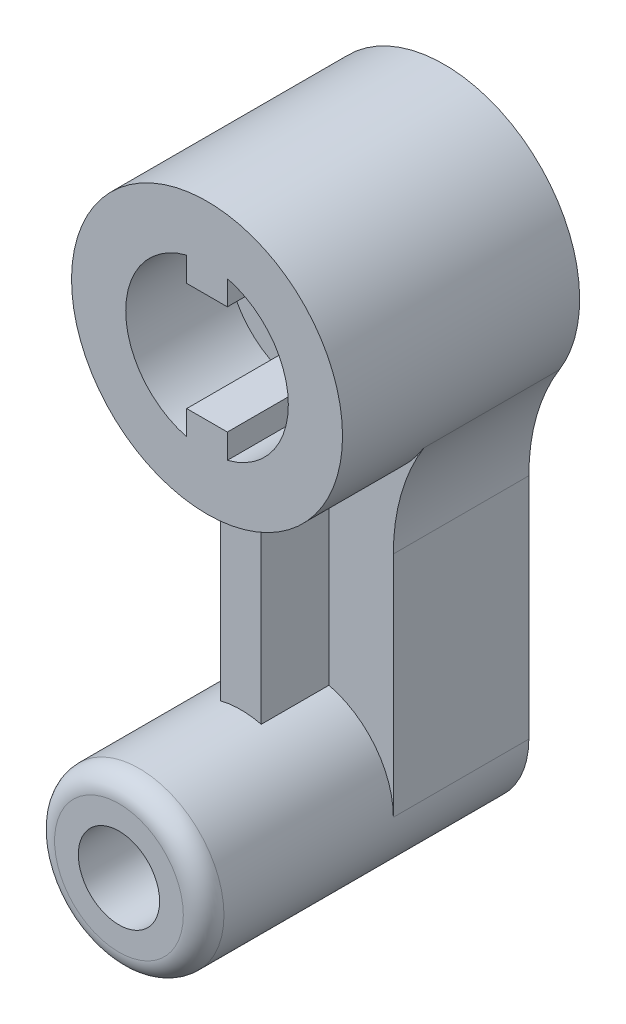
SolidWorks part; units mm, degrees
ref_plane "Alzado" through (0, 0, 0) normal (0, 0, 1) x (1, 0, 0)
ref_plane "Planta" through (0, 0, 0) normal (0, 1, 0) x (1, 0, 0)
ref_plane "Vista lateral" through (0, 0, 0) normal (1, 0, 0) x (0, 0, -1)
sketch "Croquis1" plane through (0, 0, 0) normal (0, 0, 1) x (1, 0, 0)
  line L0 (-12.5, -26.3391) -> (-12.5, -60)
  line L1 (12.5, -26.3391) -> (12.5, -60)
  line L2 (0, 28.3132) -> (0, -79.9924) construction
  arc A0 (-17, -10.5357) -> (17, -10.5357) centre (0, 0) ccw
  arc A1 (12.5, -60) -> (-12.5, -60) centre (0, -60) ccw
  arc A2 (-12.5, -26.3391) -> (-17, -10.5357) centre (-42.5, -26.3391) ccw
  arc A3 (12.5, -26.3391) -> (17, -10.5357) centre (42.5, -26.3391) cw
  dimension "D1" = 25
  dimension "D2" = 40
  dimension "D4" = 30
  dimension "D3" = 60
extrude "Saliente-Extruir1" add sketch "Croquis1" along normal blind 20
sketch "Croquis2" plane through (0, 0, 0) normal (0, 0, 1) x (1, 0, 0)
  circle A0 centre (0, 0) radius 20
  arc A1 (-17, -10.5357) -> (17, -10.5357) centre (0, 0) ccw construction
extrude "Saliente-Extruir2" add sketch "Croquis2" along normal blind 35
sketch "Croquis3" plane through (0, 0, 35) normal (0, 0, 1) x (1, 0, 0)
  line L0 (-3, 11.619) -> (-3, 8)
  line L1 (-3, 8) -> (3, 8)
  line L2 (3, 8) -> (3, 11.619)
  line L3 (-3, -11.619) -> (-3, -8)
  line L4 (-3, -8) -> (3, -8)
  line L5 (3, -8) -> (3, -11.619)
  arc A0 (-3, 11.619) -> (-3, -11.619) centre (0, 0) ccw
  arc A1 (3, -11.619) -> (3, 11.619) centre (0, 0) ccw
  dimension "D1" = 24
  dimension "D2" = 6
  dimension "D3" = 8
extrude "Cortar-Extruir1" cut sketch "Croquis3" against normal blind 15
sketch "Croquis4" plane through (0, 0, 20) normal (0, 0, 1) x (1, 0, 0)
  circle A0 centre (0, 0) radius 4
  dimension "D1" = 8
extrude "Cortar-Extruir2" cut sketch "Croquis4" against normal up to next
sketch "Croquis5" plane through (0, 0, 0) normal (0, 0, 1) x (1, 0, 0)
  circle A0 centre (0, -60) radius 12.5
  arc A1 (12.5, -60) -> (-12.5, -60) centre (0, -60) ccw construction
  circle A2 centre (0, -60) radius 6
  dimension "D1" = 12
extrude "Saliente-Extruir3" add sketch "Croquis5" along normal blind 48
fillet "Redondeo1" radius 3 1 edges at (12.5, -60, 48)
sketch "Croquis6" plane through (0, 0, 0) normal (1, 0, 0) x (0, 0, -1)
  line L0 (-30, -20) -> (-30, -47.5)
  line L1 (-35, -20) -> (-20, -20) construction
  line L2 (-20, -47.5) -> (-45, -47.5) construction
  line L3 (-20, -10.5357) -> (-20, -26.3391) construction
  dimension "D1" = 10
rib "Nervio1" sketch "Croquis6" sketch "Croquis6" thickness 6 extrusion direction parallel to sketch draft on no parameters "D1"=6
